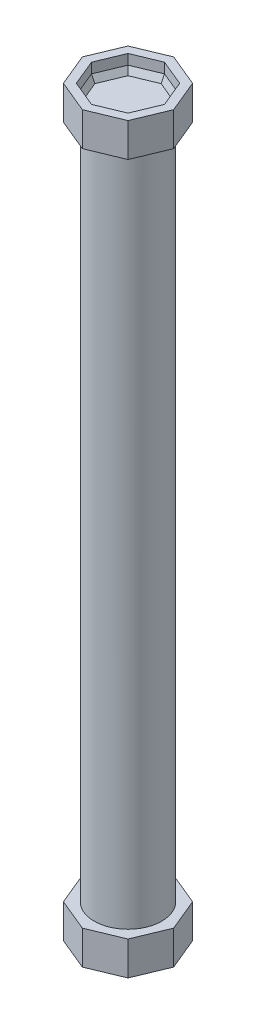
SolidWorks part; units mm, degrees
ref_plane "Front Plane" through (0, 0, 0) normal (0, 0, 1) x (1, 0, 0)
ref_plane "Top Plane" through (0, 0, 0) normal (0, 1, 0) x (1, 0, 0)
ref_plane "Right Plane" through (0, 0, 0) normal (1, 0, 0) x (0, 0, -1)
sketch "Sketch1" plane through (0, 0, 0) normal (0, 1, 0) x (1, 0, 0)
  circle A0 centre (0, 0) radius 12.7
  dimension "D1" = 25.4
extrude "Boss-Extrude1" add sketch "Sketch1" along normal blind 254
sketch "Sketch2" plane through (0, 254, 0) normal (0, 1, 0) x (1, 0, 0)
  line L1 (0, 17.183) -> (-12.1502, 12.1502)
  line L2 (-12.1502, 12.1502) -> (-17.183, 0)
  line L3 (-17.183, 0) -> (-12.1502, -12.1502)
  line L4 (-12.1502, -12.1502) -> (0, -17.183)
  line L5 (0, -17.183) -> (12.1502, -12.1502)
  line L6 (12.1502, -12.1502) -> (17.183, 0)
  line L7 (17.183, 0) -> (12.1502, 12.1502)
  line L8 (12.1502, 12.1502) -> (0, 17.183)
  circle A0 centre (0, 0) radius 15.875 construction
  dimension "D1" = 31.75
extrude "Boss-Extrude2" add sketch "Sketch2" along normal blind 12.7
sketch "Sketch3" plane through (0, 0, 0) normal (0, -1, 0) x (1, 0, 0)
  line L1 (0, 17.183) -> (-12.1502, 12.1502)
  line L2 (-12.1502, 12.1502) -> (-17.183, 0)
  line L3 (-17.183, 0) -> (-12.1502, -12.1502)
  line L4 (-12.1502, -12.1502) -> (0, -17.183)
  line L5 (0, -17.183) -> (12.1502, -12.1502)
  line L6 (12.1502, -12.1502) -> (17.183, 0)
  line L7 (17.183, 0) -> (12.1502, 12.1502)
  line L8 (12.1502, 12.1502) -> (0, 17.183)
  circle A0 centre (0, 0) radius 15.875 construction
extrude "Boss-Extrude3" add sketch "Sketch3" along normal blind 12.7
sketch "Sketch4" plane through (0, 266.7, 0) normal (0, 1, 0) x (1, 0, 0)
  line L1 (0, 13.7464) -> (-9.7202, 9.7202)
  line L2 (-9.7202, 9.7202) -> (-13.7464, 0)
  line L3 (-13.7464, 0) -> (-9.7202, -9.7202)
  line L4 (-9.7202, -9.7202) -> (0, -13.7464)
  line L5 (0, -13.7464) -> (9.7202, -9.7202)
  line L6 (9.7202, -9.7202) -> (13.7464, 0)
  line L7 (13.7464, 0) -> (9.7202, 9.7202)
  line L8 (9.7202, 9.7202) -> (0, 13.7464)
  circle A0 centre (0, 0) radius 12.7 construction
  dimension "D1" = 25.4
extrude "Cut-Extrude1" cut sketch "Sketch4" against normal blind 6.35
sketch "Sketch5" plane through (0, -12.7, 0) normal (0, -1, 0) x (1, 0, 0)
  line L1 (0, 13.7464) -> (-9.7202, 9.7202)
  line L2 (-9.7202, 9.7202) -> (-13.7464, 0)
  line L3 (-13.7464, 0) -> (-9.7202, -9.7202)
  line L4 (-9.7202, -9.7202) -> (0, -13.7464)
  line L5 (0, -13.7464) -> (9.7202, -9.7202)
  line L6 (9.7202, -9.7202) -> (13.7464, 0)
  line L7 (13.7464, 0) -> (9.7202, 9.7202)
  line L8 (9.7202, 9.7202) -> (0, 13.7464)
  circle A0 centre (0, 0) radius 12.7 construction
  dimension "D1" = 25.4
extrude "Cut-Extrude2" cut sketch "Sketch5" against normal blind 6.35
chamfer "Chamfer1" distance 2.54 angle 25 8 edges at (11.7333, -6.35, 4.8601) (11.7333, -6.35, -4.8601) (4.8601, -6.35, -11.7333) (-4.8601, -6.35, -11.7333) (-11.7333, -6.35, -4.8601) (-11.7333, -6.35, 4.8601) (-4.8601, -6.35, 11.7333) (4.8601, -6.35, 11.7333)
chamfer "Chamfer2" distance 2.54 angle 25 8 edges at (11.7333, 260.35, -4.8601) (11.7333, 260.35, 4.8601) (4.8601, 260.35, 11.7333) (-4.8601, 260.35, 11.7333) (-11.7333, 260.35, 4.8601) (-11.7333, 260.35, -4.8601) (-4.8601, 260.35, -11.7333) (4.8601, 260.35, -11.7333)
